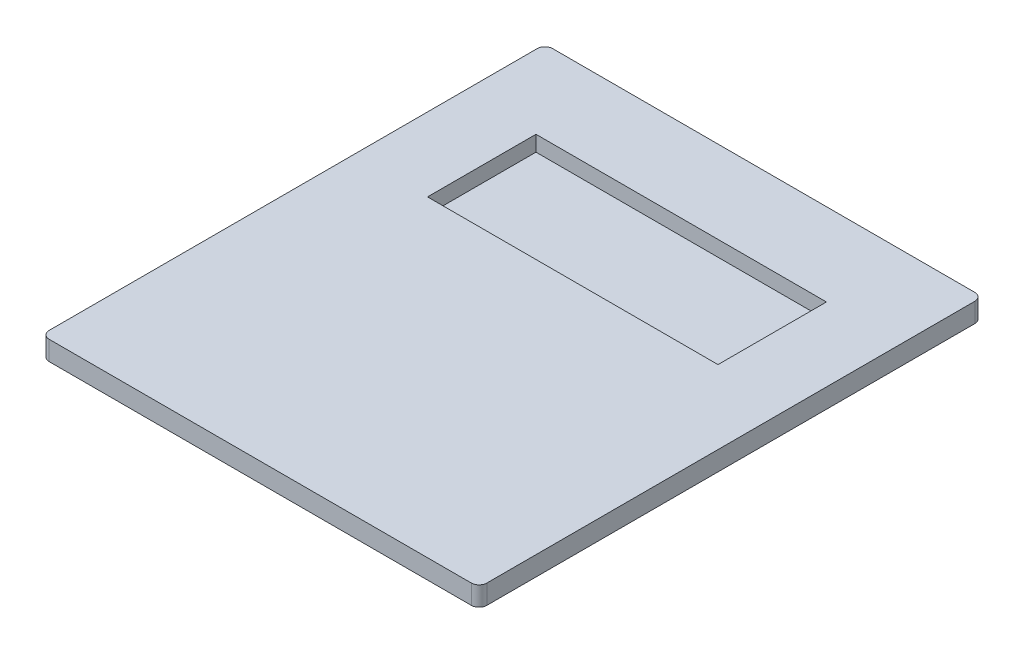
SolidWorks part; units mm, degrees
ref_plane "Front Plane" through (0, 0, 0) normal (0, 0, 1) x (1, 0, 0)
ref_plane "Top Plane" through (0, 0, 0) normal (0, 1, 0) x (1, 0, 0)
ref_plane "Right Plane" through (0, 0, 0) normal (1, 0, 0) x (0, 0, -1)
sketch "Sketch1" plane through (0, 0, 0) normal (0, 1, 0) x (1, 0, 0)
  line L1 (56.5, -65) -> (-56.5, -65)
  line L2 (56.5, -65) -> (56.5, 65)
  line L3 (56.5, 65) -> (-56.5, 65)
  line L4 (-56.5, -65) -> (-56.5, 65)
  line L5 (56.5, -65) -> (-56.5, 65) construction
  line L6 (56.5, 65) -> (-56.5, -65) construction
  point P0 (0, 0)
  dimension "D1" = 113
  dimension "D2" = 130
extrude "Boss-Extrude1" add sketch "Sketch1" along normal blind 5 contours L3 L4 L1 L2
fillet "Fillet1" radius 2 4 edges at (-56.5, 2.5, -65) (-56.5, 2.5, 65) (56.5, 2.5, -65) (56.5, 2.5, 65)
sketch "Sketch2" plane through (0, 5, 0) normal (0, 1, 0) x (1, 0, 0)
  line L0 (54.5, -65) -> (-54.5, -65) construction
  line L1 (49.5, 60) -> (-49.5, 60)
  line L2 (51.5, 58) -> (51.5, -58)
  line L3 (49.5, -60) -> (-49.5, -60)
  line L4 (-51.5, 58) -> (-51.5, -58)
  line L5 (51.5, 60) -> (-51.5, -60) construction
  line L6 (51.5, -60) -> (-51.5, 60) construction
  line L8 (56.5, -63) -> (56.5, 63) construction
  arc A0 (-49.5, -60) -> (-51.5, -58) centre (-49.5, -58) cw
  arc A1 (51.5, -58) -> (49.5, -60) centre (49.5, -58) cw
  arc A2 (51.5, 58) -> (49.5, 60) centre (49.5, 58) ccw
  arc A3 (-51.5, 58) -> (-49.5, 60) centre (-49.5, 58) cw
  point P0 (0, 0)
  dimension "D3" = 2
  dimension "D1" = 5
  dimension "D2" = 5
sketch "Sketch3" plane through (0, 5, 0) normal (0, 1, 0) x (1, 0, 0)
  line L0 (-37.5, 43.6893) -> (37.5, 43.6893)
  line L1 (-37.5, 43.6893) -> (-37.5, 15.6893)
  line L2 (37.5, 43.6893) -> (37.5, 15.6893)
  line L3 (-37.5, 15.6893) -> (37.5, 15.6893)
  line L4 (51.5, -60) -> (-51.5, 60) construction
  line L5 (51.5, 60) -> (-51.5, -60) construction
  dimension "D1" = 75
  dimension "D2" = 28
extrude "Cut-Extrude1" cut sketch "Sketch3" against normal blind 4 contours L0 L2 L3 L1
sketch "Sketch5" plane through (0, 5, 0) normal (0, 1, 0) x (1, 0, 0)
  line L0 (51.5, -60) -> (-51.5, 60) construction
  line L1 (44.4291, -51.7621) -> (-43.0087, -51.7621)
  line L2 (44.4291, -51.7621) -> (44.4291, -7.7953)
  line L3 (44.4291, -7.7953) -> (-43.0087, -7.7953)
  line L4 (-43.0087, -51.7621) -> (-43.0087, -7.7953)
